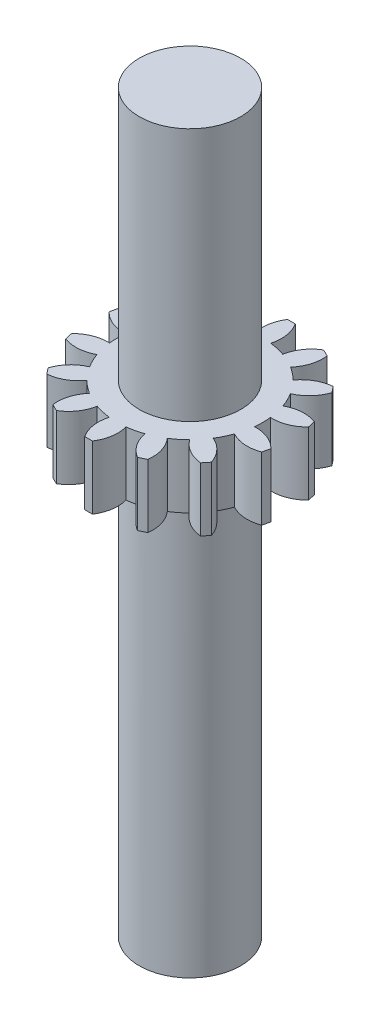
SolidWorks part; units mm, degrees
ref_plane "Front Plane" through (0, 0, 0) normal (0, 0, 1) x (1, 0, 0)
ref_plane "Top Plane" through (0, 0, 0) normal (0, 1, 0) x (1, 0, 0)
ref_plane "Right Plane" through (0, 0, 0) normal (1, 0, 0) x (0, 0, -1)
sketch "Sketch1" plane through (0, 0, 0) normal (0, 1, 0) x (1, 0, 0)
  circle A0 centre (0, 0) radius 0.4
  arc A1 (3.7449, -7.0694) -> (3.0719, -4.8595) centre (0.9684, -6.7075) ccw
  arc A2 (3.0719, -4.8595) -> (4.0541, -4.0762) centre (0, 0) ccw
  arc A3 (4.0541, -4.0762) -> (6.0588, -5.2241) centre (6.3238, -2.4367) ccw
  arc A4 (6.0588, -5.2241) -> (6.4413, -4.7444) centre (0, 0) ccw
  arc A5 (6.4413, -4.7444) -> (4.8761, -3.0454) centre (3.7828, -5.6231) ccw
  arc A6 (4.8761, -3.0454) -> (5.4212, -1.9136) centre (0, 0) ccw
  arc A7 (5.4212, -1.9136) -> (7.7254, -2.0779) centre (6.7548, 0.5485) ccw
  arc A8 (7.7254, -2.0779) -> (7.8619, -1.4798) centre (0, 0) ccw
  arc A9 (7.8619, -1.4798) -> (5.7146, -0.6281) centre (5.8479, -3.4249) ccw
  arc A10 (5.7146, -0.6281) -> (5.7146, 0.6281) centre (0, 0) ccw
  arc A11 (5.7146, 0.6281) -> (7.8619, 1.4798) centre (5.8479, 3.4249) ccw
  arc A12 (7.8619, 1.4798) -> (7.7254, 2.0779) centre (0, 0) ccw
  arc A13 (7.7254, 2.0779) -> (5.4212, 1.9136) centre (6.7548, -0.5485) ccw
  arc A14 (5.4212, 1.9136) -> (4.8761, 3.0454) centre (0, 0) ccw
  arc A15 (4.8761, 3.0454) -> (6.4413, 4.7444) centre (3.7828, 5.6231) ccw
  arc A16 (6.4413, 4.7444) -> (6.0588, 5.2241) centre (0, 0) ccw
  arc A17 (6.0588, 5.2241) -> (4.0541, 4.0762) centre (6.3238, 2.4367) ccw
  arc A18 (4.0541, 4.0762) -> (3.0719, 4.8595) centre (0, 0) ccw
  arc A19 (3.0719, 4.8595) -> (3.7449, 7.0694) centre (0.9684, 6.7075) ccw
  arc A20 (3.7449, 7.0694) -> (3.1921, 7.3355) centre (0, 0) ccw
  arc A21 (3.1921, 7.3355) -> (1.884, 5.4315) centre (4.6404, 4.9392) ccw
  arc A22 (1.884, 5.4315) -> (0.6592, 5.7111) centre (0, 0) ccw
  arc A23 (0.6592, 5.7111) -> (0.3068, 7.9941) centre (-2.0378, 6.4634) ccw
  arc A24 (0.3068, 7.9941) -> (-0.3068, 7.9941) centre (0, 0) ccw
  arc A25 (-0.3068, 7.9941) -> (-0.6592, 5.7111) centre (2.0378, 6.4634) ccw
  arc A26 (-0.6592, 5.7111) -> (-1.884, 5.4315) centre (0, 0) ccw
  arc A27 (-1.884, 5.4315) -> (-3.1921, 7.3355) centre (-4.6404, 4.9392) ccw
  arc A28 (-3.1921, 7.3355) -> (-3.7449, 7.0694) centre (0, 0) ccw
  arc A29 (-3.7449, 7.0694) -> (-3.0719, 4.8595) centre (-0.9684, 6.7075) ccw
  arc A30 (-3.0719, 4.8595) -> (-4.0541, 4.0762) centre (0, 0) ccw
  arc A31 (-4.0541, 4.0762) -> (-6.0588, 5.2241) centre (-6.3238, 2.4367) ccw
  arc A32 (-6.0588, 5.2241) -> (-6.4413, 4.7444) centre (0, 0) ccw
  arc A33 (-6.4413, 4.7444) -> (-4.8761, 3.0454) centre (-3.7828, 5.6231) ccw
  arc A34 (-4.8761, 3.0454) -> (-5.4212, 1.9136) centre (0, 0) ccw
  arc A35 (-5.4212, 1.9136) -> (-7.7254, 2.0779) centre (-6.7548, -0.5485) ccw
  arc A36 (-7.7254, 2.0779) -> (-7.8619, 1.4798) centre (0, 0) ccw
  arc A37 (-7.8619, 1.4798) -> (-5.7146, 0.6281) centre (-5.8479, 3.4249) ccw
  arc A38 (-5.7146, 0.6281) -> (-5.7146, -0.6281) centre (0, 0) ccw
  arc A39 (-5.7146, -0.6281) -> (-7.8619, -1.4798) centre (-5.8479, -3.4249) ccw
  arc A40 (-7.8619, -1.4798) -> (-7.7254, -2.0779) centre (0, 0) ccw
  arc A41 (-7.7254, -2.0779) -> (-5.4212, -1.9136) centre (-6.7548, 0.5485) ccw
  arc A42 (-5.4212, -1.9136) -> (-4.8761, -3.0454) centre (0, 0) ccw
  arc A43 (-4.8761, -3.0454) -> (-6.4413, -4.7444) centre (-3.7828, -5.6231) ccw
  arc A44 (-6.4413, -4.7444) -> (-6.0588, -5.2241) centre (0, 0) ccw
  arc A45 (-6.0588, -5.2241) -> (-4.0541, -4.0762) centre (-6.3238, -2.4367) ccw
  arc A46 (-4.0541, -4.0762) -> (-3.0719, -4.8595) centre (0, 0) ccw
  arc A47 (-3.0719, -4.8595) -> (-3.7449, -7.0694) centre (-0.9684, -6.7075) ccw
  arc A48 (-3.7449, -7.0694) -> (-3.1921, -7.3355) centre (0, 0) ccw
  arc A49 (-3.1921, -7.3355) -> (-1.884, -5.4315) centre (-4.6404, -4.9392) ccw
  arc A50 (-1.884, -5.4315) -> (-0.6592, -5.7111) centre (0, 0) ccw
  arc A51 (-0.6592, -5.7111) -> (-0.3068, -7.9941) centre (2.0378, -6.4634) ccw
  arc A52 (-0.3068, -7.9941) -> (0.3068, -7.9941) centre (0, 0) ccw
  arc A53 (0.3068, -7.9941) -> (0.6592, -5.7111) centre (-2.0378, -6.4634) ccw
  arc A54 (0.6592, -5.7111) -> (1.884, -5.4315) centre (0, 0) ccw
  arc A55 (1.884, -5.4315) -> (3.1921, -7.3355) centre (4.6404, -4.9392) ccw
  arc A56 (3.1921, -7.3355) -> (3.7449, -7.0694) centre (0, 0) ccw
extrude "Boss-Extrude1" add sketch "Sketch1" against normal blind 5
sketch "Sketch2" plane through (0, -5, 0) normal (0, -1, 0) x (1, 0, 0)
  circle A0 centre (0, 0) radius 4
  dimension "D1" = 8
extrude "Boss-Extrude2" add sketch "Sketch2" along normal blind 33 and the other way up to surface (5 mm away) other way up to face at (0, 0, -0.4)
sketch "Sketch3" plane through (0, 0, 0) normal (0, 1, 0) x (1, 0, 0)
  circle A0 centre (0, 0) radius 4
  dimension "D1" = 8
extrude "Boss-Extrude3" add sketch "Sketch3" along normal blind 20
sketch "Sketch4" plane through (0, -38, 0) normal (0, -1, 0) x (1, 0, 0)
  line L0 (-2.5, 0) -> (2.5, 0) construction
  line L1 (-2, -1.5) -> (2, -1.5)
  line L2 (-2, 1.5) -> (2, 1.5)
  line L3 (-2.5, 1.5) -> (2.5, 1.5) construction
  line L4 (-2.5, -1.5) -> (2.5, -1.5) construction
  arc A0 (-2, 1.5) -> (-2, -1.5) centre (0, 0) ccw
  arc A1 (2, -1.5) -> (2, 1.5) centre (0, 0) ccw
  point P6 (0, 0)
  dimension "D3" = 5
  dimension "D1" = 1.5
  dimension "D2" = 1.5
extrude "Cut-Extrude1" cut sketch "Sketch4" against normal up to surface (33 mm away) up to face at (0, -5, 4)
